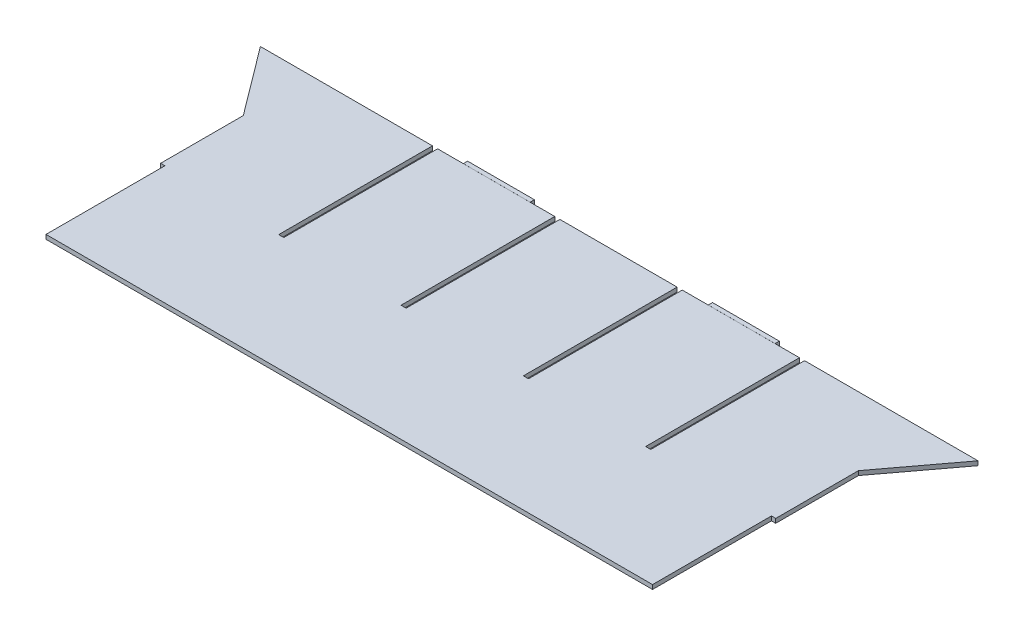
SolidWorks part; units mm, degrees
material "6061-T6 (SS)"
ref_plane "X-Y Datum" through (0, 0, 0) normal (0, 0, 1) x (1, 0, 0)
ref_plane "X-Z Datum" through (0, 0, 0) normal (0, 1, 0) x (1, 0, 0)
ref_plane "Y-Z Datum" through (0, 0, 0) normal (1, 0, 0) x (0, 0, -1)
sketch "Sketch1" plane through (0, 0, 0) normal (0, 0, 1) x (1, 0, 0)
  line L1 (-228.601, -1.5875) -> (228.601, -1.5875)
  line L2 (-228.601, -1.5875) -> (-228.601, 1.5875)
  line L3 (-228.601, 1.5875) -> (228.601, 1.5875)
  line L4 (228.601, -1.5875) -> (228.601, 1.5875)
  line L5 (-228.601, -1.5875) -> (228.601, 1.5875) construction
  line L6 (-228.601, 1.5875) -> (228.601, -1.5875) construction
  point P0 (0, 0)
  dimension "D1" = 3.175
  dimension "D2" = 457.202
extrude "Boss-Extrude1" add sketch "Sketch1" along normal blind 200.642
sketch "Sketch2" plane through (0, 1.5875, 0) normal (0, 1, 0) x (1, 0, 0)
  line L0 (228.601, 0) -> (225.426, 0)
  line L1 (228.601, 0) -> (-228.601, 0) construction
  line L2 (225.426, 0) -> (137.796, 0)
  line L3 (137.796, 0) -> (133.986, 0)
  line L10 (133.986, 0) -> (137.796, 0)
  line L11 (133.986, 0) -> (133.986, -114.3)
  line L12 (133.986, -114.3) -> (137.796, -114.3)
  line L13 (137.796, 0) -> (137.796, -114.3)
  line M2 (228.601, 0) -> (-228.601, 0)
  dimension "D1" = 87.63
  dimension "D2" = 3.175
  dimension "D3" = 114.3
extrude "Cut-Extrude1" cut sketch "Sketch2" against normal through all contours L13 L11 L12 M2
pattern_linear "LPattern1" count 4 spacing 90.932 along (-1, 0, 0) of "Cut-Extrude1"
sketch "Sketch3" plane through (0, 0, 0) normal (0, 0, -1) x (-1, 0, 0)
  line L1 (-66.1907, 1.6167) -> (-115.8495, 1.6167)
  line L2 (-66.1907, 1.6167) -> (-66.1907, -1.5583)
  line L3 (-66.1907, -1.5583) -> (-115.8495, -1.5583)
  line L4 (-115.8495, 1.6167) -> (-115.8495, -1.5583)
  line L5 (66.1907, 1.6167) -> (115.8495, 1.6167)
  line L6 (66.1907, 1.6167) -> (66.1907, -1.5583)
  line L7 (66.1907, -1.5583) -> (115.8495, -1.5583)
  line L8 (115.8495, 1.6167) -> (115.8495, -1.5583)
sketch "Sketch4" plane through (0, -1.5875, 0) normal (0, -1, 0) x (1, 0, 0)
  line L0 (-228.601, 0) -> (-266.701, 0)
  line L1 (-266.701, 0) -> (-228.601, 50.8)
  line L2 (-228.601, 200.642) -> (-228.601, 0) construction
  line L3 (-228.601, 50.8) -> (-228.601, 0)
  dimension "D1" = 38.1
  dimension "D2" = 50.8
extrude "Boss-Extrude3" add sketch "Sketch4" against normal blind 3.175
mirror "Mirror1" about plane through (0, 0, 0) normal (1, 0, 0) of "Boss-Extrude3"
sketch "Sketch5" plane through (0, -1.5875, 0) normal (0, -1, 0) x (1, 0, 0)
  line L1 (-228.601, 200.642) -> (-225.426, 200.642)
  line L2 (-228.601, 200.642) -> (-228.601, 112.25)
  line L3 (-228.601, 112.25) -> (-225.426, 112.25)
  line L4 (-225.426, 200.642) -> (-225.426, 112.25)
  dimension "D1" = 3.175
  dimension "D2" = 88.392
extrude "Cut-Extrude2" cut sketch "Sketch5" against normal blind 3.175
mirror "Mirror2" about plane through (0, 0, 0) normal (1, 0, 0) of "Cut-Extrude2"
extrude "Boss-Extrude4" add sketch "Sketch3" along normal blind 3.175
